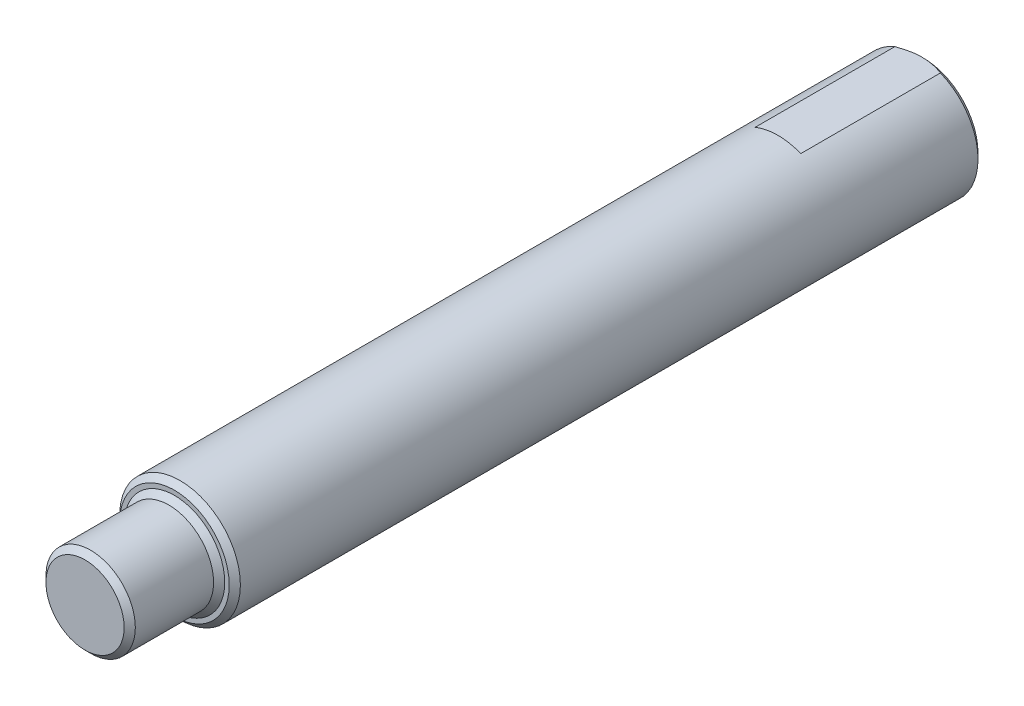
SolidWorks part; units mm, degrees
material "AISI 1045 Steel, cold drawn"
ref_plane "前视基准面" through (0, 0, 0) normal (0, 0, 1) x (1, 0, 0)
ref_plane "上视基准面" through (0, 0, 0) normal (0, 1, 0) x (1, 0, 0)
ref_plane "右视基准面" through (0, 0, 0) normal (1, 0, 0) x (0, 0, -1)
sketch "草图1" plane through (0, 0, 0) normal (0, 0, 1) x (1, 0, 0)
  circle A0 centre (0, 0) radius 5.4
  dimension "D1" = 10.8
extrude "拉伸1" add sketch "草图1" along normal blind 67
chamfer "倒角1" distance 0.5 angle 45 2 edges at (5.4, 0, 0) (5.4, 0, 67)
sketch "草图2" plane through (0, 0, 67) normal (0, 0, 1) x (1, 0, 0)
  circle A0 centre (0, 0) radius 4
  dimension "D1" = 8
extrude "拉伸2" add sketch "草图2" along normal blind 8
cosmetic thread "装饰螺纹线1" parameters "D2"=7
chamfer "倒角2" distance 0.5 angle 45 1 edges at (4, 0, 75)
hole_wizard "M5 螺纹孔1" positions "草图4" profile "草图3" tap size "M5" standard "GB"
sketch "草图4" plane through (0, 0, 0) normal (0, 0, -1) x (-1, 0, 0)
  point P1 (0, 0)
sketch "草图3" plane through (0, 0, 0) normal (1, 0, 0) x (0, 1, 0)
  line L0 (0, 0) -> (0, 13.6618)
  line L1 (0, 13.6618) -> (2.1, 12.4)
  line L2 (2.1, 12.4) -> (2.1, 0)
  line L5 (2.1, 0) -> (0, 0)
  line L10 (0, 13.6618) -> (-2.1, 12.4) construction
  line L11 (0, -6.35) -> (0, 107.95) construction
  dimension "螺纹孔钻头直径" = 4.2
  dimension "螺纹孔钻头深度" = 12.4
  dimension "导头角度" = 118
cosmetic thread "孔螺蚊线1" parameters "D1"=10, "D2"=5
chamfer "倒角3" distance 0.5 angle 45 1 edges at (-2.1, 0, 0)
sketch "草图5" plane through (0, 0, 0) normal (0, 0, 1) x (1, 0, 0)
  line L0 (0, 0) -> (0, 5) construction
  line L1 (-5, 8) -> (5, 8)
  line L2 (-5, 8) -> (-5, 5)
  line L3 (-5, 5) -> (5, 5)
  line L4 (5, 8) -> (5, 5)
  dimension "D1" = 5
  dimension "D2" = 3
  dimension "D3" = 10
extrude "拉伸3" cut sketch "草图5" along normal blind 13
mirror "镜向1" about plane through (0, 0, 0) normal (0, 1, 0) of "拉伸3"
chamfer "倒角4" distance 0.5 angle 45 1 edges at (4, 0, 67)
